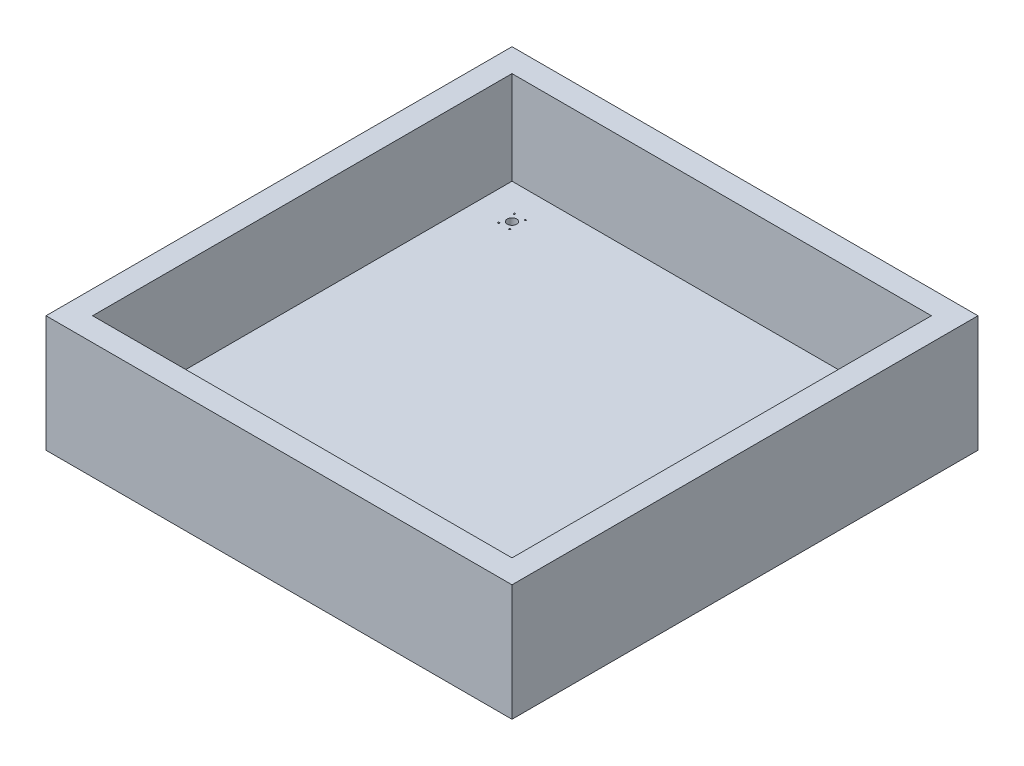
SolidWorks part; units mm, degrees
ref_plane "Front Plane" through (0, 0, 0) normal (0, 0, 1) x (1, 0, 0)
ref_plane "Top Plane" through (0, 0, 0) normal (0, 1, 0) x (1, 0, 0)
ref_plane "Right Plane" through (0, 0, 0) normal (1, 0, 0) x (0, 0, -1)
sketch "Sketch1" plane through (0, 0, 0) normal (0, 1, 0) x (1, 0, 0)
  line L0 (254, 254) -> (-254, 254)
  line L1 (228.6, -228.6) -> (-228.6, -228.6)
  line L2 (228.6, -228.6) -> (228.6, 228.6)
  line L3 (228.6, 228.6) -> (-228.6, 228.6)
  line L4 (-228.6, -228.6) -> (-228.6, 228.6)
  line L5 (228.6, -228.6) -> (-228.6, 228.6) construction
  line L6 (228.6, 228.6) -> (-228.6, -228.6) construction
  line L7 (-254, -254) -> (-254, 254)
  line L8 (254, -254) -> (-254, -254)
  line L9 (254, -254) -> (254, 254)
  point P0 (0, 0)
  dimension "D1" = 457.2
  dimension "D2" = 457.2
  dimension "D3" = 25.4
extrude "Boss-Extrude1" add sketch "Sketch1" along normal blind 101.6
sketch "Sketch2" plane through (0, 0, 0) normal (0, -1, 0) x (1, 0, 0)
  line L1 (254, -254) -> (-254, -254)
  line L2 (254, -254) -> (254, 254)
  line L3 (254, 254) -> (-254, 254)
  line L4 (-254, -254) -> (-254, 254)
  line L5 (254, -254) -> (-254, 254) construction
  line L6 (254, 254) -> (-254, -254) construction
  point P0 (0, 0)
extrude "Boss-Extrude2" add sketch "Sketch2" along normal blind 25.4
sketch "Sketch3" plane through (0, 0, 0) normal (0, 1, 0) x (1, 0, 0)
  line L0 (-196.596, 200.65) -> (-184.404, 200.65)
  line L1 (-198.12, 199.126) -> (-198.12, 181.874)
  line L2 (-196.596, 180.35) -> (-184.404, 180.35)
  line L3 (-182.88, 199.126) -> (-182.88, 181.874)
  line L4 (-228.6, 228.6) -> (-228.6, -228.6) construction
  line L5 (228.6, 228.6) -> (-228.6, 228.6) construction
  line L6 (0, 0) -> (94.6489, 0) construction
  line L7 (0, 0) -> (0, 126.8099) construction
  line L8 (182.88, 199.126) -> (182.88, 181.874)
  line L9 (196.596, 180.35) -> (184.404, 180.35)
  line L10 (198.12, 199.126) -> (198.12, 181.874)
  line L11 (196.596, 200.65) -> (184.404, 200.65)
  arc A0 (-196.596, 200.65) -> (-198.12, 199.126) centre (-196.596, 199.126) ccw
  arc A1 (-198.12, 181.874) -> (-196.596, 180.35) centre (-196.596, 181.874) ccw
  arc A2 (-184.404, 180.35) -> (-182.88, 181.874) centre (-184.404, 181.874) ccw
  arc A3 (-184.404, 200.65) -> (-182.88, 199.126) centre (-184.404, 199.126) cw
  circle A4 centre (-184.596, 182.126) radius 0.8
  circle A5 centre (-184.596, 199.126) radius 0.8
  circle A6 centre (-196.596, 199.126) radius 0.8
  circle A7 centre (-196.596, 182.126) radius 0.8
  circle A8 centre (-190.5, 190.5) radius 5.08
  circle A9 centre (190.5, 190.5) radius 5.08
  circle A10 centre (196.596, 182.126) radius 0.8
  circle A11 centre (196.596, 199.126) radius 0.8
  circle A12 centre (184.596, 199.126) radius 0.8
  circle A13 centre (184.596, 182.126) radius 0.8
  arc A14 (184.404, 200.65) -> (182.88, 199.126) centre (184.404, 199.126) ccw
  arc A15 (184.404, 180.35) -> (182.88, 181.874) centre (184.404, 181.874) cw
  arc A16 (198.12, 181.874) -> (196.596, 180.35) centre (196.596, 181.874) cw
  arc A17 (196.596, 200.65) -> (198.12, 199.126) centre (196.596, 199.126) cw
  circle A26 centre (190.5, -190.5) radius 5.08
  circle A27 centre (-190.5, -190.5) radius 5.08
  point P50 (0, 0)
  point P51 (0, 0)
  point P52 (0, 0)
  dimension "D1" = 10.15
  dimension "D2" = 1.524
  dimension "D3" = 7.62
  dimension "D4" = 12.192
  dimension "D5" = 17.252
  dimension "D6" = 38.1
  dimension "D7" = 38.1
  dimension "D8" = 12
  dimension "D9" = 17
extrude "Cut-Extrude1" cut sketch "Sketch3" against normal blind 25.4 contours A6 | A5 | A8 | A4 | A7 | A9 | A12 | A13 | A10 | A11 | A26 | A27
